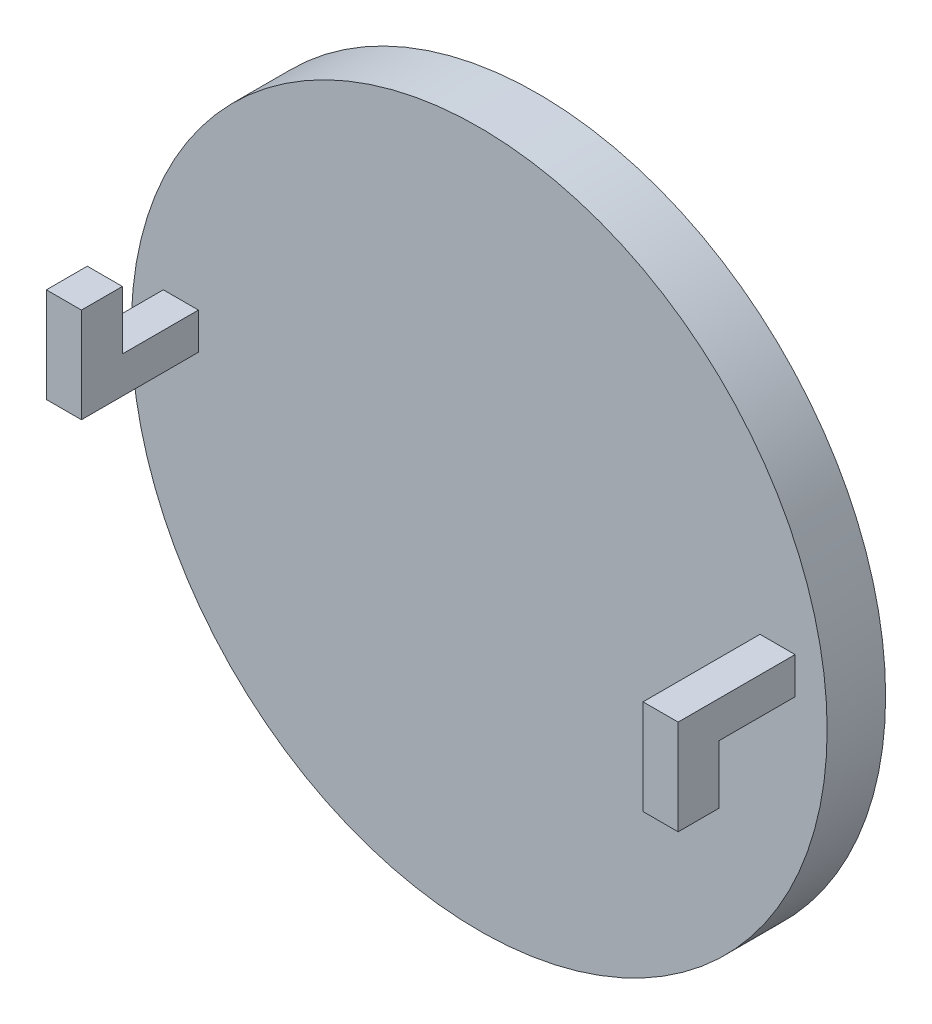
SolidWorks part; units mm, degrees
ref_plane "Front Plane" through (0, 0, 0) normal (0, 0, 1) x (1, 0, 0)
ref_plane "Top Plane" through (0, 0, 0) normal (0, 1, 0) x (1, 0, 0)
ref_plane "Right Plane" through (0, 0, 0) normal (1, 0, 0) x (0, 0, -1)
sketch "Sketch1" plane through (0, 0, 0) normal (0, 0, 1) x (1, 0, 0)
  circle A0 centre (0, 0) radius 11.9
extrude "Boss-Extrude1" add sketch "Sketch1" along normal blind 2
sketch "Sketch2" plane through (0, 0, 2) normal (0, 0, 1) x (1, 0, 0)
  line L0 (0, 0) -> (0, 4.7442) construction
  line L1 (0, 0) -> (10, 0) construction
  line L2 (10, 0) -> (10, -1.25) construction
  line L3 (9.6035, 0.4313) -> (10.8035, 0.4313)
  line L5 (9.6035, 0.4313) -> (9.6035, 1.6813)
  line L6 (9.6035, 1.6813) -> (10.8035, 1.6813)
  line L7 (10.8035, 0.4313) -> (10.8035, 1.6813)
  line L8 (9.1965, -4.1813) -> (10.8035, 1.6813) construction
  line L9 (9.6035, 1.6813) -> (10.4183, -4.3427) construction
  line L10 (-9.6035, 1.6813) -> (-10.4183, -4.3427) construction
  line L11 (-9.1965, -4.1813) -> (-10.8035, 1.6813) construction
  line L12 (-10.8035, 0.4313) -> (-10.8035, 1.6813)
  line L13 (-9.6035, 1.6813) -> (-10.8035, 1.6813)
  line L14 (-9.6035, 0.4313) -> (-9.6035, 1.6813)
  line L15 (-9.6035, 0.4313) -> (-10.8035, 0.4313)
  dimension "D1" = 10
  dimension "D2" = 1.25
  dimension "D3" = 1.25
  dimension "D4" = 1.2
extrude "Boss-Extrude2" add sketch "Sketch2" along normal blind 4
sketch "Sketch3" plane through (0, 1.6813, 0) normal (0, 1, 0) x (1, 0, 0)
  line L0 (-10.8035, -6) -> (-10.8035, -2) construction
  line L1 (-9.6035, -6) -> (-10.8035, -6)
  line L2 (-9.6035, -6) -> (-9.6035, -4.6)
  line L3 (-9.6035, -4.6) -> (-10.8035, -4.6)
  line L4 (-10.8035, -6) -> (-10.8035, -4.6)
  dimension "D1" = 1.4
extrude "Boss-Extrude3" add sketch "Sketch3" along normal blind 2
sketch "Sketch4" plane through (0, 0.4313, 0) normal (0, -1, 0) x (1, 0, 0)
  line L0 (9.6035, 6) -> (9.6035, 2) construction
  line L1 (10.8035, 6) -> (9.6035, 6)
  line L2 (10.8035, 6) -> (10.8035, 4.6)
  line L3 (10.8035, 4.6) -> (9.6035, 4.6)
  line L4 (9.6035, 6) -> (9.6035, 4.6)
  dimension "D1" = 1.4
extrude "Boss-Extrude4" add sketch "Sketch4" along normal blind 2
